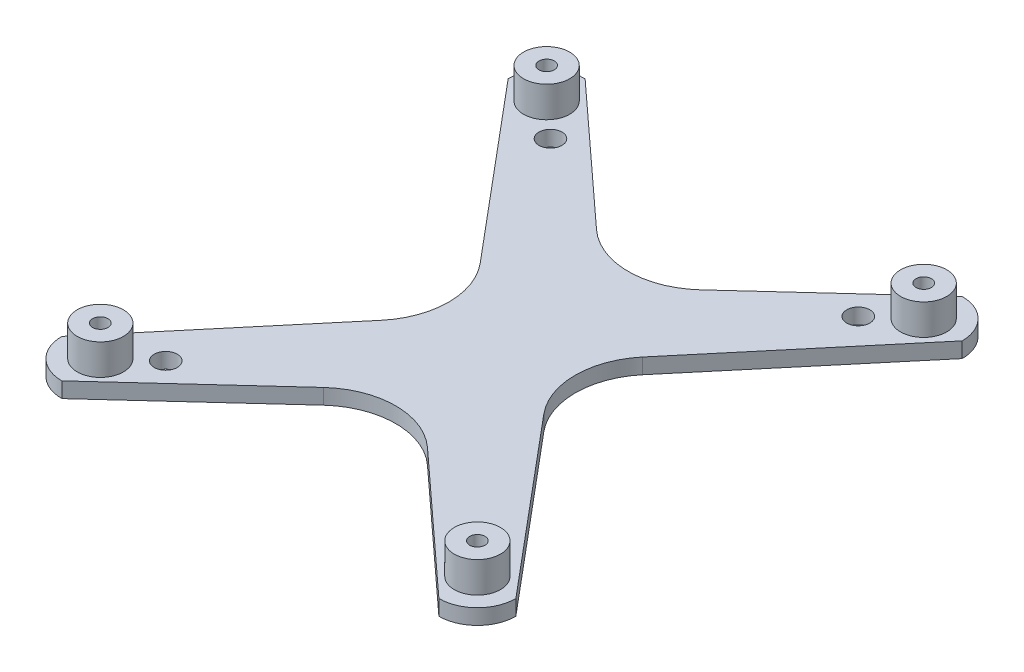
SolidWorks part; units mm, degrees
ref_plane "Front Plane" through (0, 0, 0) normal (0, 0, 1) x (1, 0, 0)
ref_plane "Top Plane" through (0, 0, 0) normal (0, 1, 0) x (1, 0, 0)
ref_plane "Right Plane" through (0, 0, 0) normal (1, 0, 0) x (0, 0, -1)
sketch "Sketch1" plane through (0, 0, 0) normal (0, 1, 0) x (1, 0, 0)
  line L0 (5, 5) -> (54, 63) construction
  line L1 (0, 0) -> (59, 0)
  line L2 (0, 0) -> (0, 68)
  line L3 (0, 68) -> (59, 68)
  line L4 (59, 0) -> (59, 68)
  line L5 (9.5, 59) -> (49.5, 59) construction
  line L6 (9.5, 59) -> (9.5, 9) construction
  line L7 (9.5, 9) -> (49.5, 9) construction
  line L8 (49.5, 59) -> (49.5, 9) construction
  line L9 (5, 5) -> (54, 5) construction
  line L10 (5, 5) -> (5, 63) construction
  line L11 (5, 63) -> (54, 63) construction
  line L12 (54, 5) -> (54, 63) construction
  line L13 (54, 5) -> (5, 63) construction
  line L14 (49.5, 59) -> (9.5, 9) construction
  line L15 (9.5, 59) -> (49.5, 9) construction
  circle A0 centre (5, 5) radius 1
  circle A1 centre (54, 5) radius 1
  circle A2 centre (5, 63) radius 1
  circle A3 centre (54, 63) radius 1
  circle A4 centre (9.5, 59) radius 1.5
  circle A5 centre (49.5, 59) radius 1.5
  circle A6 centre (49.5, 9) radius 1.5
  circle A7 centre (9.5, 9) radius 1.5
  point P18 (29.5, 34)
  point P22 (29.5, 34)
  dimension "D1" = 2
  dimension "D10" = 3
  dimension "D11" = 3
  dimension "D12" = 3
  dimension "D13" = 3
  dimension "D6" = 5
  dimension "D7" = 50
  dimension "D8" = 49
  dimension "D9" = 5
  dimension "D14" = 40
  dimension "D15" = 58
  dimension "D16" = 5
  dimension "D17" = 5
extrude "Boss-Extrude1" add sketch "Sketch1" along normal blind 2
fillet "Fillet1" radius 5 4 edges at (0, 1, -68) (0, 1, 0) (59, 1, -68) (59, 1, 0)
sketch "Sketch2" plane through (0, 2, 0) normal (0, 1, 0) x (1, 0, 0)
  line L0 (0, 5) -> (18.9403, 27.5721)
  line L1 (18.9403, 40.4279) -> (0, 63)
  line L2 (54, 0) -> (36.2559, 16.2595)
  line L3 (22.7441, 16.2595) -> (5, 0)
  line L4 (54, 68) -> (5, 68)
  line L5 (0, 63) -> (0, 5)
  line L6 (5, 0) -> (54, 0)
  line L7 (59, 5) -> (59, 63)
  line L8 (54, 68) -> (5, 68)
  line L9 (0, 63) -> (0, 5)
  line L10 (5, 0) -> (54, 0)
  line L11 (59, 5) -> (59, 63)
  line L12 (59, 5) -> (40.0597, 27.5721)
  line L13 (40.0597, 40.4279) -> (59, 63)
  line L14 (54, 68) -> (36.2559, 51.7405)
  line L15 (22.7441, 51.7405) -> (5, 68)
  arc A0 (36.2559, 16.2595) -> (22.7441, 16.2595) centre (29.5, 8.8867) ccw
  arc A1 (40.0597, 27.5721) -> (40.0597, 40.4279) centre (47.7202, 34) cw
  arc A2 (36.2559, 51.7405) -> (22.7441, 51.7405) centre (29.5, 59.1133) cw
  arc A3 (18.9403, 27.5721) -> (18.9403, 40.4279) centre (11.2798, 34) ccw
  arc A4 (5, 68) -> (0, 63) centre (5, 63) ccw
  arc A5 (0, 5) -> (5, 0) centre (5, 5) ccw
  arc A6 (54, 0) -> (59, 5) centre (54, 5) ccw
  arc A7 (59, 63) -> (54, 68) centre (54, 63) ccw
  dimension "D6" = 10
  dimension "D2" = 100
  dimension "D3" = 100
  dimension "D4" = 95
  dimension "D5" = 95
  dimension "D1" = 0
extrude "Cut-Extrude1" cut sketch "Sketch2" against normal blind 2
sketch "Sketch3" plane through (0, 2, 0) normal (0, 1, 0) x (1, 0, 0)
  circle A0 centre (5, 63) radius 3
  circle A1 centre (54, 63) radius 3
  circle A2 centre (54, 5) radius 3
  circle A3 centre (5, 5) radius 3
  circle A4 centre (5, 63) radius 1
  circle A5 centre (54, 63) radius 1
  circle A6 centre (54, 5) radius 1
  circle A7 centre (5, 5) radius 1
  circle A8 centre (5, 63) radius 1 construction
extrude "Boss-Extrude2" add sketch "Sketch3" along normal blind 4
